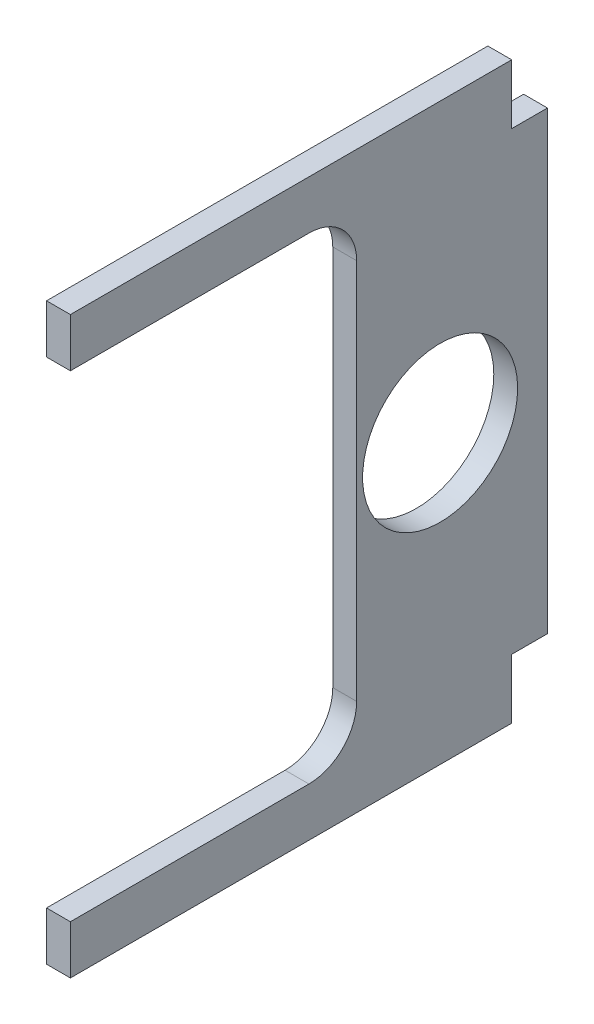
SolidWorks part; units mm, degrees
material "PVC rigido"
ref_plane "Piano frontale" through (0, 0, 0) normal (0, 0, 1) x (1, 0, 0)
ref_plane "Piano superiore" through (0, 0, 0) normal (0, 1, 0) x (1, 0, 0)
ref_plane "Piano destro" through (0, 0, 0) normal (1, 0, 0) x (0, 0, -1)
sketch "Schizzo1" plane through (0, 0, 0) normal (0, 0, 1) x (1, 0, 0)
  line L0 (-239, 19.0864) -> (-239, -19.0864) construction
  line L1 (-239, 19.0864) -> (-239, -19.0864)
  line L3 (-241, -19.0864) -> (-241, 19.0864) construction
  line L4 (-239, -19.0864) -> (-241, -19.0864) construction
  line L5 (-241, 19.0864) -> (-239, 19.0864)
  line L6 (-241, -19.0864) -> (-241, 19.0864)
  line L7 (-239, -19.0864) -> (-241, -19.0864)
extrude "Estrusione-Estrusione1" add sketch "Schizzo1" along normal up to surface (13 mm away) and the other way up to surface (3 mm away)
ref_plane "Piano1" through (0, 0, 0) normal (0, 1, 0) x (1, 0, 0)
sketch "Schizzo2" plane through (0, 19.0864, 0) normal (0, 1, 0) x (1, 0, 0)
  line L0 (-239, -13) -> (-239, 3) construction
  line L1 (-241, 0) -> (-239, 0)
  line L2 (-241, 0) -> (-241, -37)
  line L3 (-241, -37) -> (-239, -37)
  line L4 (-239, 0) -> (-239, -37)
  line L6 (-238, -37) -> (-242, -37) construction
extrude "Estrusione-Estrusione2" add sketch "Schizzo2" along normal blind 5
sketch "Schizzo3" plane through (-239, 0, 0) normal (1, 0, 0) x (0, 0, -1)
  line L0 (-37, 24.0864) -> (-37, 19.0864) construction
  line L1 (-13, 19.0864) -> (-37, 19.0864)
  line L2 (-13, 19.0864) -> (-13, 20)
  line L3 (-13, 20) -> (-37, 20)
  line L4 (-37, 19.0864) -> (-37, 20)
  line L5 (-17, 20) -> (-46, 20) construction
extrude "Taglio-Estrusione1" cut sketch "Schizzo3" against normal blind 10
fillet "Raccordo1" radius 4 1 edges at (-240, 20, 13)
mirror "Specchia1" about plane through (0, 0, 0) normal (0, 1, 0) of "Raccordo1", "Taglio-Estrusione1", "Estrusione-Estrusione2"
sketch "Schizzo4" plane through (-239, 0, 0) normal (1, 0, 0) x (0, 0, -1)
  line L0 (3, 0) -> (-13, 0) construction
  line L1 (3, -19.0864) -> (3, 19.0864) construction
  line L2 (-13, -16) -> (-13, 16) construction
  circle A0 centre (-6, 0) radius 6.5
  dimension "D1" = 13
  dimension "D2" = 7
extrude "Taglio-Estrusione2" cut sketch "Schizzo4" against normal blind 10
